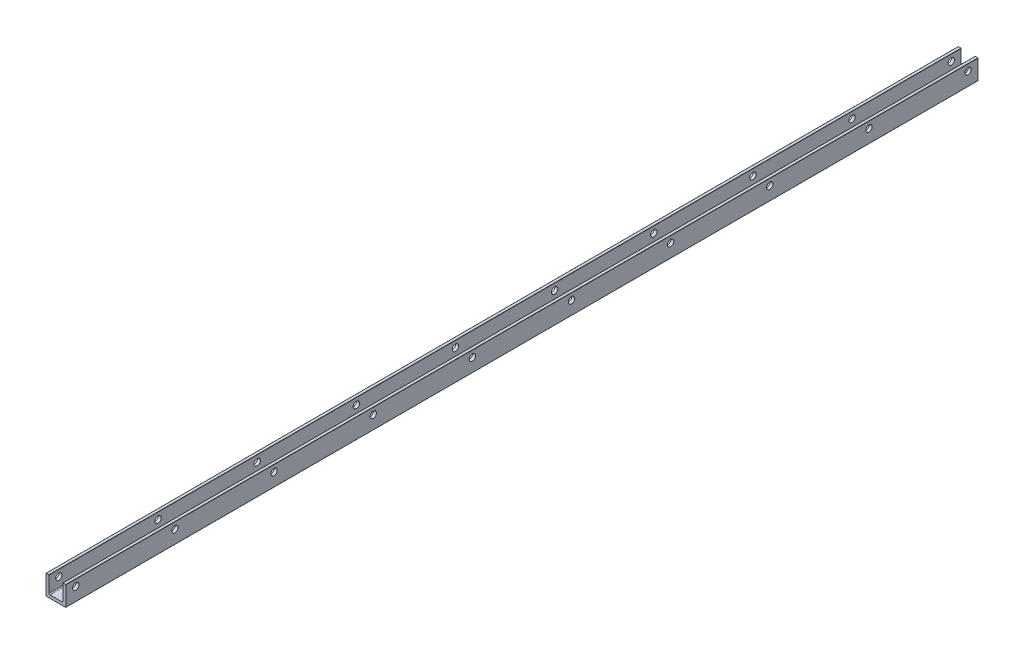
SolidWorks part; units mm, degrees
ref_plane "Front Plane" through (0, 0, 0) normal (0, 0, 1) x (1, 0, 0)
ref_plane "Top Plane" through (0, 0, 0) normal (0, 1, 0) x (1, 0, 0)
ref_plane "Right Plane" through (0, 0, 0) normal (1, 0, 0) x (0, 0, -1)
sketch "Sketch1" plane through (0, 0, 0) normal (0, 0, 1) x (1, 0, 0)
  line L0 (0, 0) -> (0, 13962.1943) construction
  line L1 (-5, 0) -> (5, 0)
  line L2 (5, 0) -> (5, 10)
  line L3 (5, 10) -> (3.5, 10)
  line L4 (3.5, 10) -> (3.5, 1.5)
  line L5 (3.5, 1.5) -> (-3.5, 1.5)
  line L6 (-3.5, 10) -> (-3.5, 1.5)
  line L7 (-5, 10) -> (-3.5, 10)
  line L8 (-5, 0) -> (-5, 10)
  point P9 (0, 0)
  point P11 (0, 1.5)
  point P14 (0, 0)
  dimension "D1" = 5
  dimension "D2" = 10
  dimension "D3" = 1.5
  dimension "D4" = 1.5
extrude "Boss-Extrude1" add sketch "Sketch1" along normal blind 460
fillet "Fillet1" radius 0.5 2 edges at (-3.5, 1.5, 230) (3.5, 1.5, 230)
fillet "Fillet2" radius 0.1 6 edges at (5, 0, 230) (-5, 0, 230) (5, 10, 230) (3.5, 10, 230) (-3.5, 10, 230) (-5, 10, 230)
sketch "Sketch2" plane through (-5, 0, 0) normal (-1, 0, 0) x (0, 0, 1)
  line L0 (460, 9.9) -> (0, 9.9) construction
  line L1 (0, 9.9) -> (0, 0.1) construction
  circle A0 centre (5, 6.7) radius 1.6
  circle A1 centre (55, 6.7) radius 1.6
  circle A2 centre (105, 6.7) radius 1.6
  circle A3 centre (155, 6.7) radius 1.6
  circle A4 centre (205, 6.7) radius 1.6
  circle A5 centre (255, 6.7) radius 1.6
  circle A6 centre (305, 6.7) radius 1.6
  circle A7 centre (355, 6.7) radius 1.6
  circle A8 centre (405, 6.7) radius 1.6
  circle A9 centre (455, 6.7) radius 1.6
  circle A10 centre (505, 6.7) radius 1.6
  dimension "D1" = 3.2
  dimension "D2" = 3.2
  dimension "D3" = 5
  dimension "D4" = 11
extrude "Cut-Extrude1" cut sketch "Sketch2" against normal through all
sketch "Sketch4" plane through (0, 0, 0) normal (0, -1, 0) x (1, 0, 0)
  line L0 (0, 0) -> (0, 50000) construction
  circle A0 centre (0, 30) radius 2.7
  dimension "D1" = 30
  dimension "D2" = 5.4
extrude "Cut-Extrude2" cut sketch "Sketch4" against normal through all
